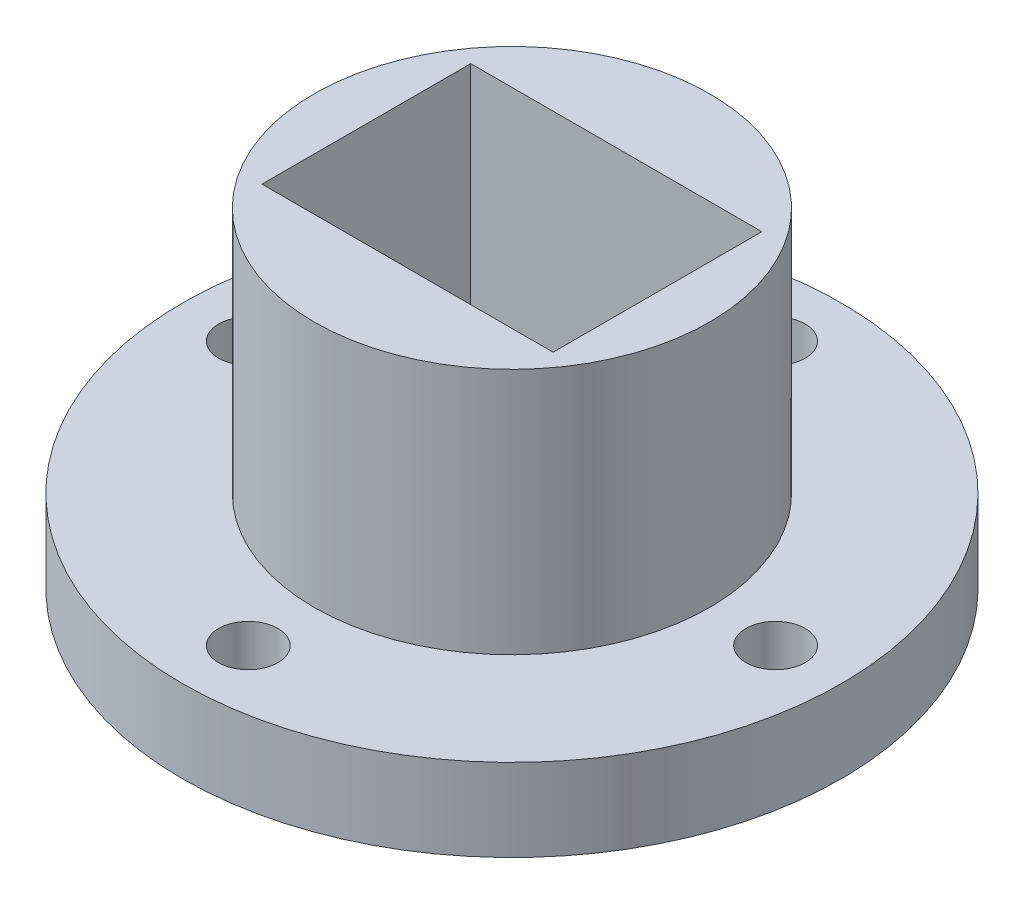
SolidWorks part; units mm, degrees
ref_plane "Front Plane" through (0, 0, 0) normal (0, 0, 1) x (1, 0, 0)
ref_plane "Top Plane" through (0, 0, 0) normal (0, 1, 0) x (1, 0, 0)
ref_plane "Right Plane" through (0, 0, 0) normal (1, 0, 0) x (0, 0, -1)
sketch "Sketch1" plane through (0, 0, 0) normal (0, 1, 0) x (1, 0, 0)
  line L1 (-2.65, -1.9) -> (2.65, -1.9)
  line L2 (-2.65, -1.9) -> (-2.65, 1.9)
  line L3 (-2.65, 1.9) -> (2.65, 1.9)
  line L4 (2.65, -1.9) -> (2.65, 1.9)
  line L5 (-2.65, -1.9) -> (2.65, 1.9) construction
  line L6 (-2.65, 1.9) -> (2.65, -1.9) construction
  circle A0 centre (0, 0) radius 6
  dimension "D1" = 5.3
  dimension "D3" = 12
  dimension "D2" = 3.8
extrude "Boss-Extrude1" add sketch "Sketch1" along normal blind 6
sketch "Sketch6" plane through (0, 0, 0) normal (1, 0, 0) x (0, 0, -1)
  line L0 (0, 6) -> (0, 0) construction
  line L1 (-6, 6) -> (-3.6, 6)
  line L2 (-6, 6) -> (-6, 1.5)
  line L3 (-6, 1.5) -> (-3.6, 1.5)
  line L4 (-3.6, 6) -> (-3.6, 1.5)
  line L5 (-1.9, 6) -> (1.9, 6) construction
  dimension "D1" = 2.4
  dimension "D2" = 4.5
revolve "Cut-Revolve1" cut sketch "Sketch6" angle 360 about L0
sketch "Sketch10" plane through (0, 1.5, 0) normal (0, 1, 0) x (1, 0, 0)
  line L0 (-6, 0) -> (-3.6, 0) construction
  line L1 (3.6, 0) -> (6, 0) construction
  line L3 (0, -3.6) -> (0, -6) construction
  circle A0 centre (0, 0) radius 6 construction
  circle A1 centre (0, 0) radius 3.6 construction
  circle A2 centre (0, 0) radius 3.6 construction
  circle A3 centre (-4.8, 0) radius 0.54
  circle A4 centre (0, -4.8) radius 0.54
  circle A5 centre (4.8, 0) radius 0.54
  circle A6 centre (0, 4.8) radius 0.54
  dimension "D1" = 1.08
  dimension "D2" = 1.08
  dimension "D3" = 1.08
  dimension "D4" = 1.08
extrude "Cut-Extrude2" cut sketch "Sketch10" against normal blind 60
